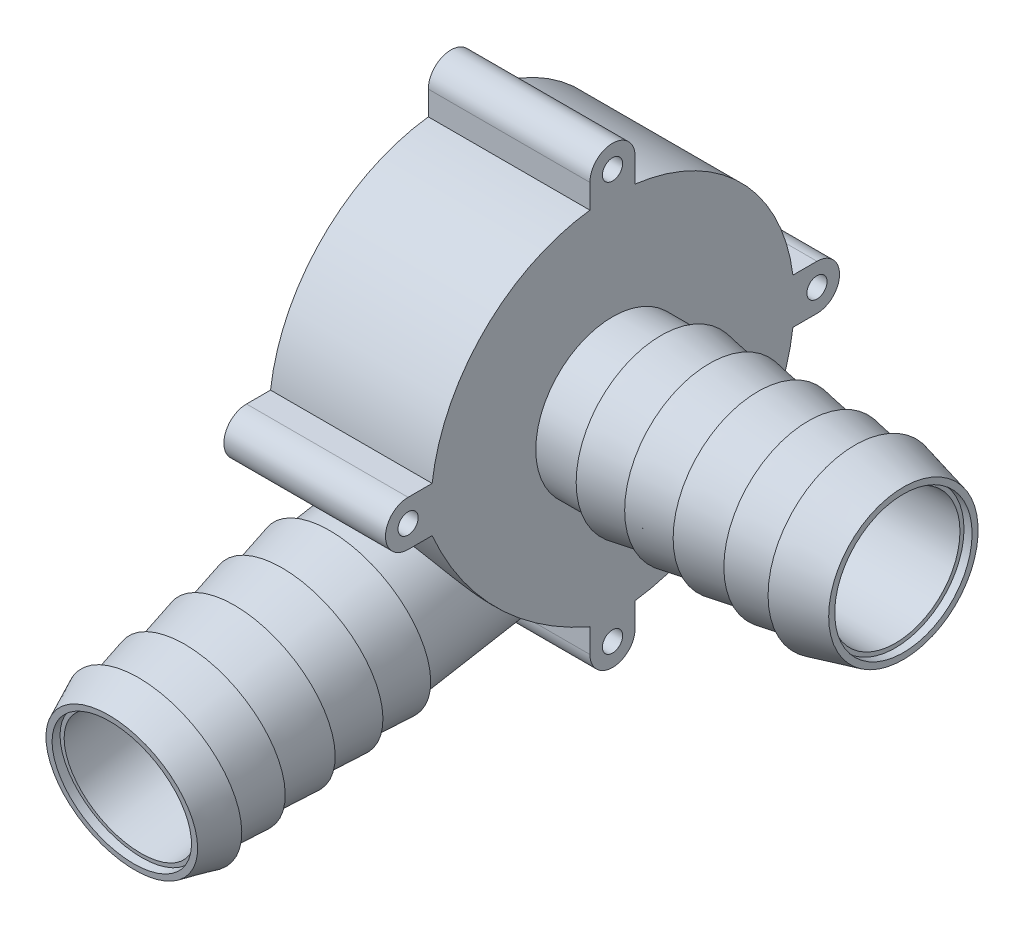
SolidWorks part; units mm, degrees
ref_plane "Спереди" through (0, 0, 0) normal (0, 0, 1) x (1, 0, 0)
ref_plane "Сверху" through (0, 0, 0) normal (0, 1, 0) x (1, 0, 0)
ref_plane "Справа" through (0, 0, 0) normal (1, 0, 0) x (0, 0, -1)
sketch "Эскиз1" plane through (0, 0, 0) normal (0, 0, 1) x (1, 0, 0)
  line L2 (0, 0) -> (39.0949, 0) construction
  line L3 (6, 9.5) -> (6, 10.5)
  line L5 (12, 10.5) -> (12, 9.5)
  line L6 (12, 9.5) -> (6, 10.5)
  line L8 (18, 10.5) -> (18, 9.5)
  line L9 (18, 9.5) -> (12, 10.5)
  line L11 (24.2385, 10.4602) -> (24.2385, 9.4602)
  line L12 (24.2385, 9.4602) -> (18, 10.5)
  line L14 (30, 10.75) -> (30, 9.5)
  line L15 (30, 9.5) -> (24.2385, 10.4602)
  line L19 (36, 9.25) -> (36, 8)
  line L20 (36, 8) -> (0, 8)
  line L21 (0, 9.5) -> (0, 8)
  line L22 (6, 9.5) -> (0, 9.5)
  line L23 (6, 9.5) -> (30, 9.5) construction
  line L24 (30, 10.75) -> (36, 9.25)
revolve "Повернуть1" add sketch "Эскиз1" angle 360 about L2
sketch "Эскиз2" plane through (0, 0, 0) normal (-1, 0, 0) x (0, 0, 1)
  circle A0 centre (0, 0) radius 22.5
extrude "Бобышка-Вытянуть1" add sketch "Эскиз2" along normal blind 20
sketch "Эскиз3" plane through (36, 0, 0) normal (1, 0, 0) x (0, 0, -1)
  circle A0 centre (0, 0) radius 8
  circle A1 centre (0, 0) radius 8.5
extrude "Вырез-Вытянуть1" cut sketch "Эскиз3" against normal blind 1
sketch "Эскиз4" plane through (0, 0, 0) normal (1, 0, 0) x (0, 0, -1)
  line L0 (25.3, 2.8) -> (22.3251, 2.8)
  line L1 (-2.8, 25.3) -> (-2.8, 22.3251)
  line L2 (2.8, 25.3) -> (2.8, 22.3251)
  line L3 (25.3, -2.8) -> (22.3251, -2.8)
  line L4 (2.8, -25.3) -> (2.8, -22.3251)
  line L5 (-2.8, -25.3) -> (-2.8, -22.3251)
  line L6 (-25.3, -2.8) -> (-22.3251, -2.8)
  line L7 (-25.3, 2.8) -> (-22.3251, 2.8)
  circle A0 centre (0, 0) radius 22.5 construction
  arc A1 (2.8, 22.3251) -> (-2.8, 22.3251) centre (0, 0) ccw
  arc A2 (2.8, 25.3) -> (-2.8, 25.3) centre (0, 25.3) ccw
  arc A3 (22.3251, -2.8) -> (22.3251, 2.8) centre (0, 0) ccw
  arc A4 (25.3, -2.8) -> (25.3, 2.8) centre (25.3, 0) ccw
  arc A5 (-2.8, -22.3251) -> (2.8, -22.3251) centre (0, 0) ccw
  arc A6 (-2.8, -25.3) -> (2.8, -25.3) centre (0, -25.3) ccw
  arc A7 (-22.3251, 2.8) -> (-22.3251, -2.8) centre (0, 0) ccw
  arc A8 (-25.3, 2.8) -> (-25.3, -2.8) centre (-25.3, 0) ccw
  point P26 (0, 0)
  dimension "D1" = 4
extrude "Бобышка-Вытянуть2" add sketch "Эскиз4" against normal up to surface (20 mm away) up to face at (-20, 0, 22.5)
hole_wizard "Отверстие обработанное метчиком M31" positions "Эскиз5" profile "Эскиз6" tap size "M3" standard "ISO" end condition through all
sketch "Эскиз5" plane through (0, 0, 0) normal (1, 0, 0) x (0, 0, -1)
  point P0 (0, 25.3)
  point P15 (-25.3, 0)
  point P18 (0, -25.3)
  point P21 (25.3, 0)
cosmetic thread "Отверстие резьбы1" parameters "D2"=3
cosmetic thread "Отверстие резьбы2" parameters "D2"=3
cosmetic thread "Отверстие резьбы3" parameters "D2"=3
cosmetic thread "Отверстие резьбы4" parameters "D2"=3
sketch "Эскиз6" plane through (0, 25.3, 0) normal (0, 1, 0) x (0, 0, -1)
  line L0 (0, 0) -> (0, 20)
  line L1 (0, 20) -> (1.25, 20)
  line L2 (1.25, 20) -> (1.25, 0)
  line L5 (1.25, 0) -> (0, 0)
  line L11 (0, -6.35) -> (0, 107.95) construction
  dimension "Диаметр проходного сверла" = 2.5
  dimension "Глубина проходного сверла" = 20
sketch "Эскиз7" plane through (0, 0, 0) normal (1, 0, 0) x (0, 0, -1)
  arc A0 (-22.3251, -2.8) -> (-2.8, -22.3251) centre (12.1018, 12.1018) ccw
  arc A1 (-22.3251, -2.8) -> (-2.8, -22.3251) centre (0, 0) ccw construction
  arc A2 (-22.3251, -2.8) -> (-2.8, -22.3251) centre (0, 0) ccw
extrude "Вырез-Вытянуть2" cut sketch "Эскиз7" against normal through all
ref_plane "Плоскость1" through (0, -1.152, 6.5334) normal (0, -0.1736, 0.9848) x (1, 0, 0)
sketch "Эскиз9" plane through (0, -1.152, 6.5334) normal (0, -0.1736, 0.9848) x (1, 0, 0)
  circle A0 centre (-10, -11.9997) radius 9.5
extrude "Бобышка-Вытянуть4" add sketch "Эскиз9" along normal blind 19
ref_plane "Плоскость2" through (-10, 0, 0) normal (1, 0, 0) x (0, 0, -1)
sketch "Эскиз10" plane through (-10, 0, 0) normal (1, 0, 0) x (0, 0, -1)
  line L0 (-23.161, -16.2687) -> (-63.6316, -23.4048) construction
  line L2 (-27.2465, -27.6511) -> (-27.4202, -26.6663)
  line L3 (-27.4202, -26.6663) -> (-21.3377, -26.6092)
  line L4 (-33.1554, -28.693) -> (-33.329, -27.7082)
  line L5 (-33.329, -27.7082) -> (-27.2465, -27.6511)
  line L6 (-39.306, -29.7372) -> (-39.4797, -28.7523)
  line L7 (-39.4797, -28.7523) -> (-33.1554, -28.693)
  line L8 (-44.9297, -31.023) -> (-45.1467, -29.792)
  line L9 (-45.1467, -29.792) -> (-39.306, -29.7372)
  line L10 (-49.1294, -30.2404) -> (-49.3464, -29.0094)
  line L14 (-21.5113, -25.6244) -> (-45.1467, -29.792) construction
  line L15 (-44.9297, -31.023) -> (-49.1294, -30.2404)
  line L16 (-49.3464, -29.0094) -> (-21.7718, -24.1472)
  line L17 (-24.8107, -6.9131) -> (-21.5113, -25.6244) construction
  line L19 (-21.3377, -26.6092) -> (-21.7718, -24.1472)
  dimension "D1" = 28
revolve "Повернуть2" add sketch "Эскиз10" angle 360 about L0
sketch "Эскиз12" plane through (-20, 0, 0) normal (-1, 0, 0) x (0, 0, 1)
  arc A3 (20.3739, -2.2699) -> (2.2699, -20.3739) centre (0, 0) ccw
  arc A4 (2.2699, -20.3739) -> (20.3739, -2.2699) centre (-12.1018, 12.1018) ccw
extrude "Вырез-Вытянуть3" cut sketch "Эскиз12" against normal blind 18
sketch "Эскиз13" plane through (0, -9.3135, 52.8194) normal (0, -0.1736, 0.9848) x (1, 0, 0)
  circle A2 centre (-10, -11.9997) radius 8
  circle A3 centre (-10, -11.9997) radius 8.5
sketch "Эскиз14" plane through (0, -4.4513, 25.2447) normal (0, -0.1736, 0.9848) x (1, 0, 0)
  circle A1 centre (-10, -11.9997) radius 8
  circle A2 centre (-10, -11.9997) radius 8
  dimension "D1" = 0
extrude "Вырез-Вытянуть5" cut sketch "Эскиз14" against normal blind 21
sketch "Эскиз15" plane through (0, 0, 0) normal (1, 0, 0) x (0, 0, -1)
  circle A0 centre (0, 0) radius 8
extrude "Вырез-Вытянуть6" cut sketch "Эскиз15" against normal blind 21
extrude "Вырез-Вытянуть7" cut sketch "Эскиз13" against normal blind 1
